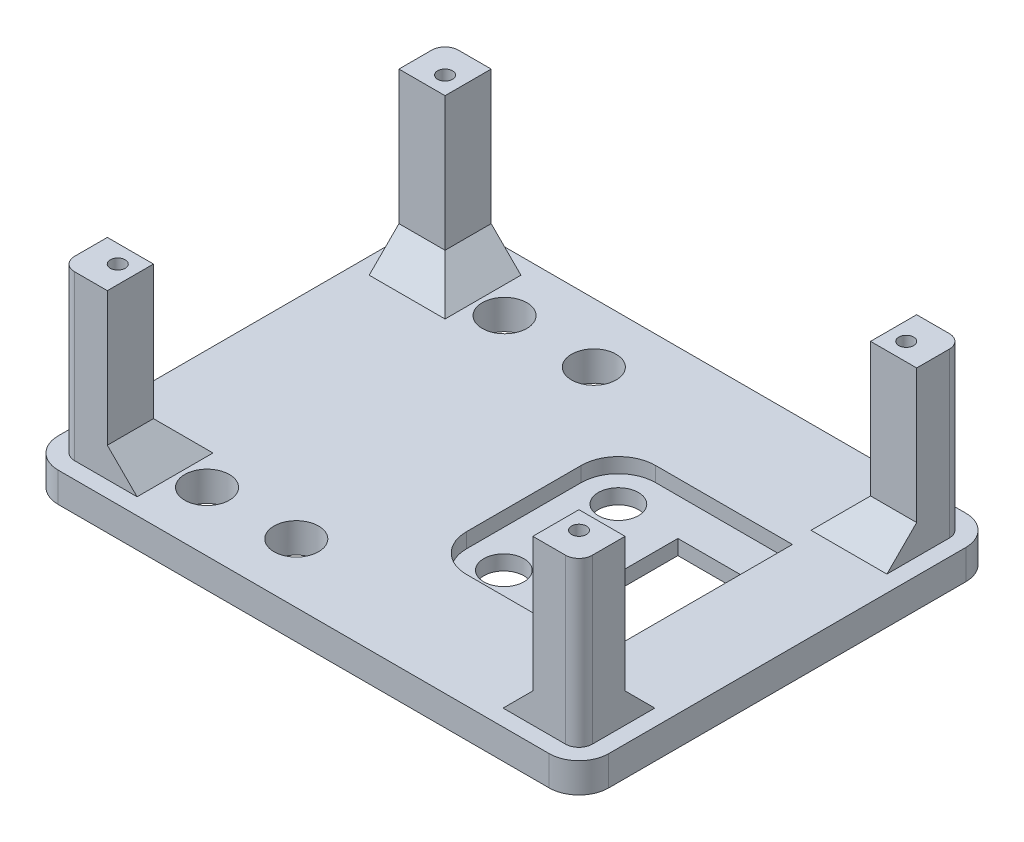
SolidWorks part; units mm, degrees
ref_plane "Front Plane" through (0, 0, 0) normal (0, 0, 1) x (1, 0, 0)
ref_plane "Top Plane" through (0, 0, 0) normal (0, 1, 0) x (1, 0, 0)
ref_plane "Right Plane" through (0, 0, 0) normal (1, 0, 0) x (0, 0, -1)
sketch "Sketch1" plane through (0, 0, 0) normal (0, 1, 0) x (1, 0, 0)
  line L1 (0, 0) -> (93.98, 0)
  line L2 (0, 0) -> (0, 71.12)
  line L3 (0, 71.12) -> (93.98, 71.12)
  line L4 (93.98, 0) -> (93.98, 71.12)
  dimension "D1" = 93.98
  dimension "D2" = 71.12
extrude "Boss-Extrude1" add sketch "Sketch1" along normal blind 5.08
sketch "Sketch2" plane through (0, 5.08, 0) normal (0, 1, 0) x (1, 0, 0)
  line L0 (46.99, 71.12) -> (46.99, 0) construction
  line L1 (2.794, 68.326) -> (10.668, 68.326)
  line L2 (2.794, 68.326) -> (2.794, 60.452)
  line L3 (2.794, 60.452) -> (10.668, 60.452)
  line L4 (10.668, 68.326) -> (10.668, 60.452)
  line L17 (93.98, 71.12) -> (0, 71.12) construction
  line L18 (0, 0) -> (93.98, 0) construction
  line L19 (0, 35.56) -> (93.98, 35.56) construction
  line L20 (0, 71.12) -> (0, 0) construction
  line L21 (93.98, 0) -> (93.98, 71.12) construction
  line L22 (83.312, 68.326) -> (83.312, 60.452)
  line L23 (91.186, 60.452) -> (83.312, 60.452)
  line L24 (91.186, 68.326) -> (91.186, 60.452)
  line L25 (91.186, 68.326) -> (83.312, 68.326)
  line L26 (91.186, 2.794) -> (83.312, 2.794)
  line L27 (91.186, 2.794) -> (91.186, 10.668)
  line L28 (91.186, 10.668) -> (83.312, 10.668)
  line L29 (83.312, 2.794) -> (83.312, 10.668)
  line L30 (10.668, 2.794) -> (10.668, 10.668)
  line L31 (2.794, 10.668) -> (10.668, 10.668)
  line L32 (2.794, 2.794) -> (2.794, 10.668)
  line L33 (2.794, 2.794) -> (10.668, 2.794)
  dimension "D1" = 7.874
  dimension "D2" = 7.874
  dimension "D3" = 2.794
  dimension "D4" = 2.794
fillet "Fillet4" radius 5.08 4 edges at (0, 2.54, -71.12) (93.98, 2.54, -71.12) (93.98, 2.54, 0) (0, 2.54, 0)
sketch "Sketch7" plane through (0, 5.08, 0) normal (0, 1, 0) x (1, 0, 0)
  line L0 (65.532, 35.56) -> (78.74, 35.56) construction
  line L1 (65.532, 45.339) -> (78.74, 45.339)
  line L2 (65.532, 45.339) -> (65.532, 25.781)
  line L3 (65.532, 25.781) -> (78.74, 25.781)
  line L4 (78.74, 45.339) -> (78.74, 25.781)
  circle A0 centre (55.372, 45.339) radius 3.429
  circle A1 centre (55.372, 25.781) radius 3.429
  dimension "D1" = 6.858
  dimension "D2" = 6.858
  dimension "D3" = 19.558
  dimension "D4" = 13.208
  dimension "D5" = 10.16
  dimension "D6" = 30.48
  dimension "D7" = 15.24
extrude "Cut-Extrude5" cut sketch "Sketch7" against normal up to next
sketch "Sketch8" plane through (0, 5.08, 0) normal (0, 1, 0) x (1, 0, 0)
  line L0 (5.08, 0) -> (88.9, 0) construction
  line L3 (0, 35.56) -> (93.98, 35.56) construction
  line L4 (0, 66.04) -> (0, 5.08) construction
  line L5 (93.98, 5.08) -> (93.98, 66.04) construction
  circle A2 centre (20.32, 10.16) radius 3.81
  circle A3 centre (35.56, 10.16) radius 3.81
  circle A4 centre (35.56, 60.96) radius 3.81
  circle A5 centre (20.32, 60.96) radius 3.81
  dimension "D1" = 15.24
  dimension "D2" = 7.62
  dimension "D4" = 7.62
  dimension "D3" = 10.16
  dimension "D5" = 15.24
sketch "Sketch9" plane through (0, 5.08, 0) normal (0, 1, 0) x (1, 0, 0)
  line L0 (55.372, 45.339) -> (55.372, 25.781) construction
  line L2 (49.022, 45.339) -> (49.022, 25.781)
  line L4 (65.532, 51.689) -> (78.74, 51.689)
  line L6 (65.532, 19.431) -> (78.74, 19.431)
  line L7 (78.74, 51.689) -> (78.74, 19.431)
  line L10 (78.74, 25.781) -> (78.74, 45.339) construction
  line L11 (55.372, 19.431) -> (65.532, 19.431)
  line L12 (55.372, 51.689) -> (65.532, 51.689)
  arc A0 (55.372, 51.689) -> (49.022, 45.339) centre (55.372, 45.339) ccw
  arc A1 (49.022, 25.781) -> (55.372, 19.431) centre (55.372, 25.781) ccw
  point P4 (55.372, 35.56)
  dimension "D2" = 6.35
  dimension "D3" = 6.35
extrude "Cut-Extrude7" cut sketch "Sketch9" against normal blind 2.54
extrude "Cut-Extrude8" cut sketch "Sketch8" against normal up to next
extrude "Boss-Extrude3" add sketch "Sketch2" along normal blind 30.48
sketch "Sketch10" plane through (0, 35.56, 0) normal (0, 1, 0) x (1, 0, 0)
  line L0 (46.99, 71.12) -> (46.99, 0) construction
  line L1 (88.9, 71.12) -> (5.08, 71.12) construction
  line L2 (5.08, 0) -> (88.9, 0) construction
  line L3 (0, 35.56) -> (93.98, 35.56) construction
  line L4 (0, 66.04) -> (0, 5.08) construction
  line L5 (93.98, 5.08) -> (93.98, 66.04) construction
  circle A0 centre (7.62, 63.5) radius 1.27
  circle A1 centre (86.36, 63.5) radius 1.27
  circle A2 centre (86.36, 7.62) radius 1.27
  circle A3 centre (7.62, 7.62) radius 1.27
  dimension "D1" = 7.62
  dimension "D3" = 2.54
  dimension "D2" = 7.62
extrude "Cut-Extrude9" cut sketch "Sketch10" against normal blind 12.7
fillet "Fillet5" radius 2.286 4 edges at (91.186, 20.32, -68.326) (91.186, 20.32, -2.794) (2.794, 20.32, -2.794) (2.794, 20.32, -68.326)
chamfer "Chamfer4" distance 5.08 angle 45 8 edges at (87.249, 5.08, -10.668) (83.312, 5.08, -6.731) (87.249, 5.08, -60.452) (83.312, 5.08, -64.389) (10.668, 5.08, -6.731) (6.731, 5.08, -10.668) (10.668, 5.08, -64.389) (6.731, 5.08, -60.452)
sketch "Sketch11" plane through (0, 35.56, 0) normal (0, 1, 0) x (1, 0, 0)
  line L1 (99.3383, -3.677) -> (-4.1971, -3.677)
  line L2 (99.3383, -3.677) -> (99.3383, 74.41)
  line L3 (99.3383, 74.41) -> (-4.1971, 74.41)
  line L4 (-4.1971, -3.677) -> (-4.1971, 74.41)
extrude "Cut-Extrude10" cut sketch "Sketch11" against normal blind 2.54
